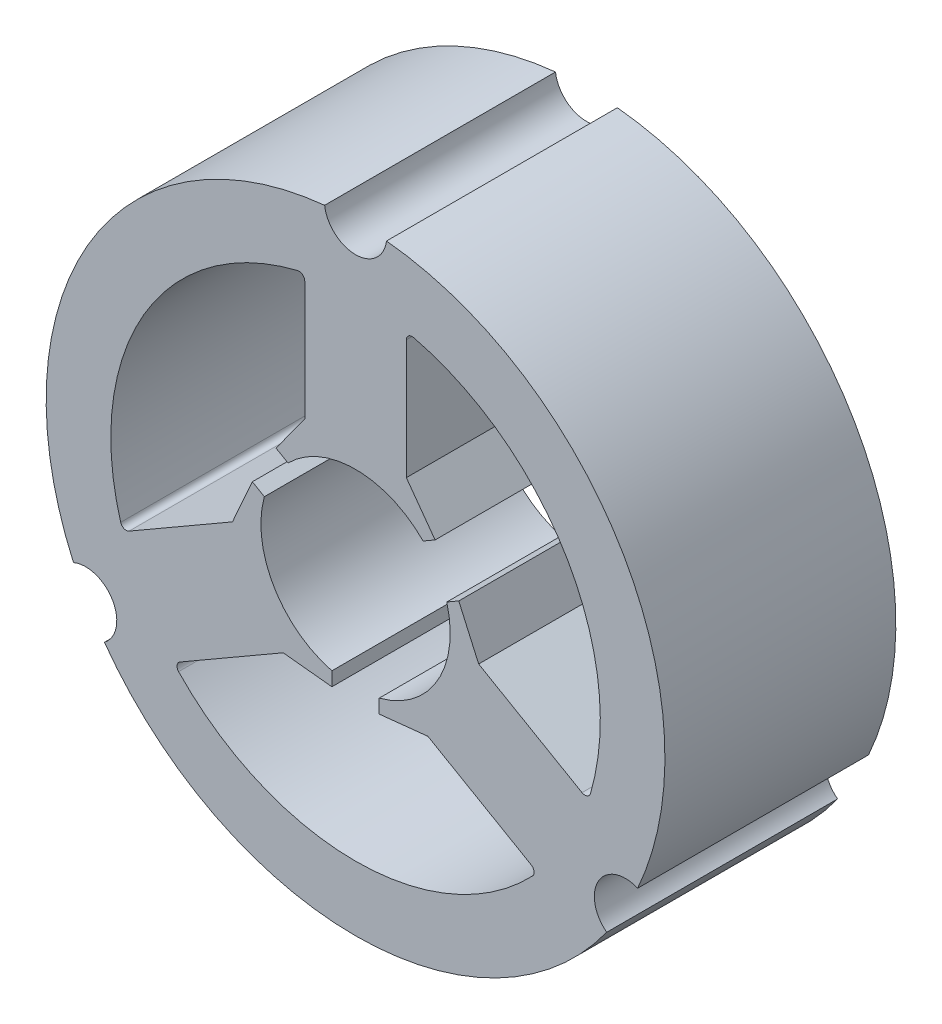
SolidWorks part; units mm, degrees
ref_plane "前视基准面" through (0, 0, 0) normal (0, 0, 1) x (1, 0, 0)
ref_plane "上视基准面" through (0, 0, 0) normal (0, 1, 0) x (1, 0, 0)
ref_plane "右视基准面" through (0, 0, 0) normal (1, 0, 0) x (0, 0, -1)
sketch "草图1" plane through (0, 0, 0) normal (0, 0, 1) x (1, 0, 0)
  line L0 (-21.4536, 0) -> (25.5305, 0) construction
  line L1 (0, 19.7631) -> (0, -19.5145) construction
  line L14 (-0.6212, 13.5) -> (0.4164, 13.5) construction
  line L15 (12.0019, -6.2121) -> (11.4831, -7.1106) construction
  line L16 (-11.3808, -7.2879) -> (-11.8995, -6.3894) construction
  line L17 (0, 0) -> (14.054, -8.1141) construction
  line L18 (0, 0) -> (-15.2933, -8.8296) construction
  circle A1 centre (0, 0) radius 4.1
  arc A7 (-1.3396, 13.3329) -> (-12.2164, -5.5063) centre (0, 0) ccw
  arc A8 (-1.3396, 13.3329) -> (1.3396, 13.3329) centre (0, 13.5) ccw
  arc A9 (12.2164, -5.5063) -> (10.8768, -7.8266) centre (11.6913, -6.75) ccw
  arc A10 (-10.8768, -7.8266) -> (-12.2164, -5.5063) centre (-11.6913, -6.75) ccw
  arc A11 (12.2164, -5.5063) -> (1.3396, 13.3329) centre (0, 0) ccw
  arc A12 (-10.8768, -7.8266) -> (10.8768, -7.8266) centre (0, 0) ccw
  point P24 (0, 0)
  point P31 (0, 0)
  dimension "D1" = 26.8
  dimension "D2" = 8.2
  dimension "D3" = 1.35
  dimension "D4" = 13.5
  dimension "D7" = 120
  dimension "D5" = 3
  dimension "D6" = 120
extrude "凸台-拉伸1" add sketch "草图1" along normal blind 10
sketch "草图2" plane through (0, 0, 0) normal (0, 0, 1) x (1, 0, 0)
  line L0 (-18.2914, 0) -> (18.1831, 0) construction
  line L1 (0, 18.2481) -> (0, -17.8941) construction
  line L2 (0, 0) -> (17.302, -9.9893) construction
  line L3 (-7.6086, -6.9332) -> (-3.1316, -4.3484)
  line L4 (-3.1316, -4.3484) -> (-1.025, -4.5698)
  line L5 (0, 0) -> (-16.8155, -9.7084) construction
  line L6 (-1.025, -4.5698) -> (-1.025, -3.9698)
  line L7 (1.025, -4.5698) -> (1.025, -3.9698)
  line L8 (3.1316, -4.3484) -> (1.025, -4.5698)
  line L9 (7.6086, -6.9332) -> (3.1316, -4.3484)
  arc A0 (-7.6644, -7.3224) -> (7.6644, -7.3224) centre (0, 0) ccw
  arc A3 (7.6644, -7.3224) -> (7.6086, -6.9332) centre (7.4836, -7.1497) ccw
  arc A4 (-7.6644, -7.3224) -> (-7.6086, -6.9332) centre (-7.4836, -7.1497) cw
  arc A7 (-1.025, -3.9698) -> (1.025, -3.9698) centre (0, 0) ccw
  point P19 (1.025, -4.2698)
  point P21 (7.88, -7.0898)
  point P24 (-7.88, -7.0898)
  dimension "D2" = 21.2
  dimension "D8" = 0.25
  dimension "D11" = 0.25
  dimension "D1" = 120
  dimension "D3" = 120
  dimension "D4" = 2.2
  dimension "D5" = 144
  dimension "D6" = 2.05
  dimension "D7" = 0.6
  dimension "D9" = 2.2
  dimension "D10" = 60
extrude "切除-拉伸1" cut sketch "草图2" along normal blind 10
pattern_circular "阵列(圆周)1" count 3 over 360 about axis through (0, 0, 0) along (0, 0, 1) of "切除-拉伸1"
